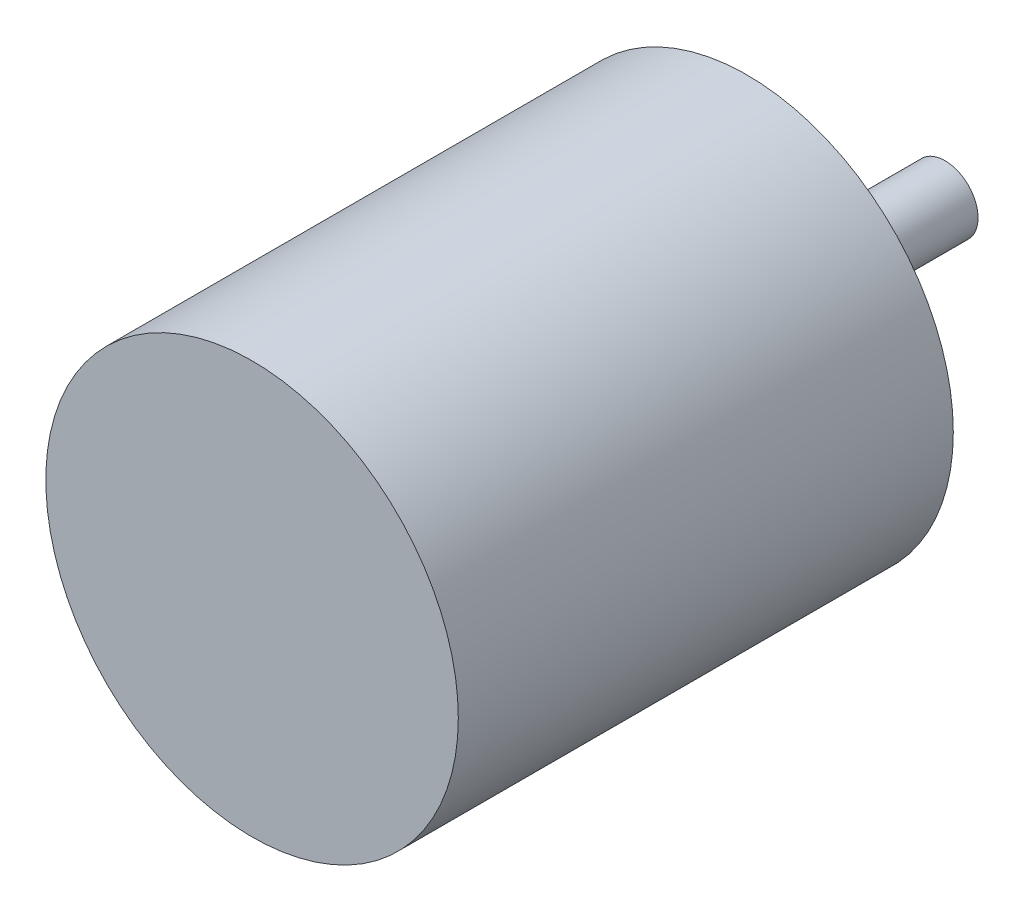
SolidWorks part; units mm, degrees
ref_plane "前视基准面" through (0, 0, 0) normal (0, 0, 1) x (1, 0, 0)
ref_plane "上视基准面" through (0, 0, 0) normal (0, 1, 0) x (1, 0, 0)
ref_plane "右视基准面" through (0, 0, 0) normal (1, 0, 0) x (0, 0, -1)
sketch "草图1" plane through (0, 0, 0) normal (0, 0, 1) x (1, 0, 0)
  circle A0 centre (0, 0) radius 12.5
  point P0 (0, 0)
  dimension "D1" = 25
extrude "凸台-拉伸3" add sketch "草图1" along normal blind 30
sketch "草图3" plane through (0, 0, 0) normal (0, 0, -1) x (-1, 0, 0)
  circle A1 centre (8.5, 0) radius 1.5
  circle A2 centre (-8.5, 0) radius 1.5
  dimension "D1" = 3
  dimension "D2" = 3
  dimension "D3" = 17
  dimension "D4" = 8.5
extrude "切除-拉伸1" cut sketch "草图3" against normal blind 15
sketch "草图4" plane through (0, 0, 0) normal (0, 0, -1) x (-1, 0, 0)
  circle A0 centre (0, 0) radius 6
  dimension "D1" = 12
extrude "凸台-拉伸4" add sketch "草图4" along normal blind 2
sketch "草图5" plane through (0, 0, -2) normal (0, 0, -1) x (-1, 0, 0)
  circle A0 centre (0, 0) radius 2
  dimension "D1" = 4
extrude "凸台-拉伸5" add sketch "草图5" along normal blind 10
